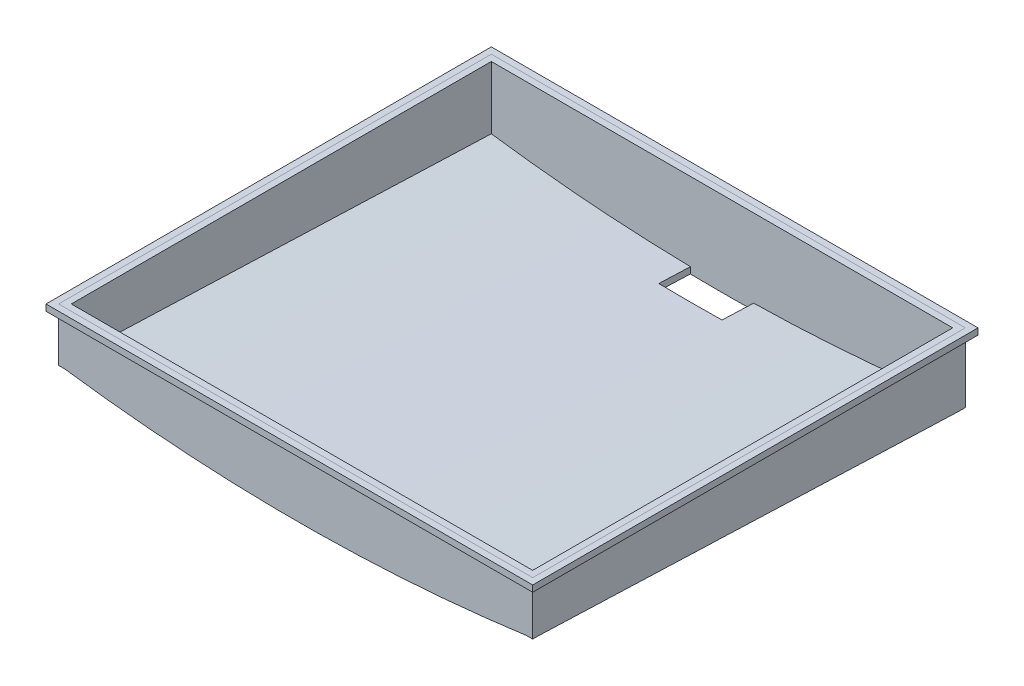
SolidWorks part; units mm, degrees
ref_plane "Front Plane" through (0, 0, 0) normal (0, 0, 1) x (1, 0, 0)
ref_plane "Top Plane" through (0, 0, 0) normal (0, 1, 0) x (1, 0, 0)
ref_plane "Right Plane" through (0, 0, 0) normal (1, 0, 0) x (0, 0, -1)
sketch "Sketch1" plane through (0, 0, 0) normal (0, 0, 1) x (1, 0, 0)
  line L0 (0, 0) -> (-73, 0) construction
  line L1 (0, 0) -> (73, 0) construction
  line L2 (0, 0) -> (0, -5) construction
  line L3 (73, 0) -> (73, -2.0188)
  line L4 (-73, 0) -> (-73, -2.0188)
  arc A0 (73, 0) -> (-73, 0) centre (0, 530.4) cw
  arc A1 (73, -2.0188) -> (-73, -2.0188) centre (0, 530.4) cw
  arc A3 (73.2727, -1.9813) -> (-73.2727, -1.9813) centre (0, 530.4) cw construction
  dimension "D1" = 2
sketch "Sketch2" plane through (0, 0, 0) normal (1, 0, 0) x (0, 0, -1)
  line L0 (0, 0) -> (133, 0) construction
  line L2 (133, 0) -> (133, -5) construction
  line L3 (133, -5) -> (0, 0) construction
extrude "Boss-Extrude1" add sketch "Sketch1" along direction (0, 0.0376, 0.9993) on the side against the normal blind 133
sketch "Sketch3" plane through (-73, 0, 0) normal (-1, 0, 0) x (0, 0, 1)
  line L0 (-132.9061, -4.9965) -> (-132.9061, 14.8275)
  line L1 (-132.9061, 14.8275) -> (0, 14.8275)
  line L2 (0, 14.8275) -> (0, -2.0188)
  line L3 (0, -2.0188) -> (-132.9061, -7.0153)
  line L4 (-132.9061, -7.0153) -> (-132.9061, -4.9965)
extrude "Boss-Extrude2" add sketch "Sketch3" along normal blind 2
pattern_linear "LPattern1" count 2 spacing 148 along (1, 0, 0) of "Boss-Extrude2"
sketch "Sketch6" plane through (0, 0, 0) normal (0, 0, 1) x (1, 0, 0)
  line L0 (-73, 14.8275) -> (73, 14.8275)
  line L9 (-73, 0) -> (-73, 14.8275)
  line L10 (-73, 14.8275) -> (-75, 14.8275)
  line L11 (-75, 14.8275) -> (-75, -2.0188)
  line L12 (-75, -2.0188) -> (-73, -2.0188)
  line L13 (73, -2.0188) -> (75, -2.0188)
  line L14 (75, -2.0188) -> (75, 14.8275)
  line L15 (75, 14.8275) -> (73, 14.8275)
  line L16 (73, 14.8275) -> (73, 0)
  line L18 (-73, 14.8275) -> (-75, 14.8275)
  line L19 (-75, 14.8275) -> (-75, -2.0188)
  line L20 (-75, -2.0188) -> (-73, -2.0188)
  line L21 (73, -2.0188) -> (75, -2.0188)
  line L22 (75, -2.0188) -> (75, 14.8275)
  line L23 (75, 14.8275) -> (73, 14.8275)
  arc A2 (-73, 0) -> (73, 0) centre (0, 530.4) ccw
  arc A3 (-73, -2.0188) -> (73, -2.0188) centre (0, 530.4) ccw
  arc A5 (-73, -2.0188) -> (73, -2.0188) centre (0, 530.4) ccw
  dimension "D1" = 0
extrude "Boss-Extrude3" add sketch "Sketch6" along normal blind 2
sketch "Sketch7" plane through (0, 0, -132.9061) normal (0, 0, -1) x (-1, 0, 0)
  line L0 (-73, 14.8275) -> (73, 14.8275)
  line L9 (-73, -4.9965) -> (-73, 14.8275)
  line L10 (-73, 14.8275) -> (-75, 14.8275)
  line L11 (-75, 14.8275) -> (-75, -7.0153)
  line L12 (-75, -7.0153) -> (-73, -7.0153)
  line L13 (73, -7.0153) -> (75, -7.0153)
  line L14 (75, -7.0153) -> (75, 14.8275)
  line L15 (75, 14.8275) -> (73, 14.8275)
  line L16 (73, 14.8275) -> (73, -4.9965)
  line L18 (-73, 14.8275) -> (-75, 14.8275)
  line L19 (-75, 14.8275) -> (-75, -7.0153)
  line L20 (-75, -7.0153) -> (-73, -7.0153)
  line L21 (73, -7.0153) -> (75, -7.0153)
  line L22 (75, -7.0153) -> (75, 14.8275)
  line L23 (75, 14.8275) -> (73, 14.8275)
  arc A2 (-73, -4.9965) -> (73, -4.9965) centre (0, 525.4035) ccw
  arc A3 (-73, -7.0153) -> (73, -7.0153) centre (0, 525.4035) ccw
  arc A5 (-73, -7.0153) -> (73, -7.0153) centre (0, 525.4035) ccw
  dimension "D1" = 0
extrude "Boss-Extrude4" add sketch "Sketch7" along normal blind 2
ref_plane "Plane1" through (75, 14.8275, 2) normal (0, 0, -1) x (-1, 0, 0)
ref_plane "Plane2" through (0, 14.8275, 0) normal (0, 1, 0) x (1, 0, 0)
sketch "Sketch10" plane through (0, 14.8275, 0) normal (0, 1, 0) x (1, 0, 0)
  line L0 (112.6492, -2) -> (37.3508, -2) construction
  line L1 (-75, 134.9061) -> (75, 134.9061)
  line L2 (-75, 134.9061) -> (-75, -2)
  line L3 (-75, -2) -> (75, -2)
  line L4 (75, 134.9061) -> (75, -2)
  line L5 (75, -2) -> (75, 134.9061) construction
  line L6 (-77, 136.9061) -> (-77, -4)
  line L7 (-77, -4) -> (77, -4)
  line L8 (77, 136.9061) -> (77, -4)
  line L9 (-77, 136.9061) -> (77, 136.9061)
  dimension "D1" = 2
extrude "Boss-Extrude5" add sketch "Sketch10" against normal blind 2 separate body
sketch "Sketch11" plane through (0, 14.8275, 0) normal (0, 1, 0) x (1, 0, 0)
  line L0 (0, 133) -> (0, 0) construction
  line L1 (10, 122.9061) -> (-10, 122.9061)
  line L2 (10, 122.9061) -> (10, 132.9061)
  line L3 (10, 132.9061) -> (-10, 132.9061)
  line L4 (-10, 122.9061) -> (-10, 132.9061)
  line L5 (10, 122.9061) -> (-10, 132.9061) construction
  line L6 (10, 132.9061) -> (-10, 122.9061) construction
  line L7 (-73, 132.9061) -> (73, 132.9061) construction
  point P0 (0, 127.9061)
extrude "Cut-Extrude1" cut sketch "Sketch11" against normal through all
